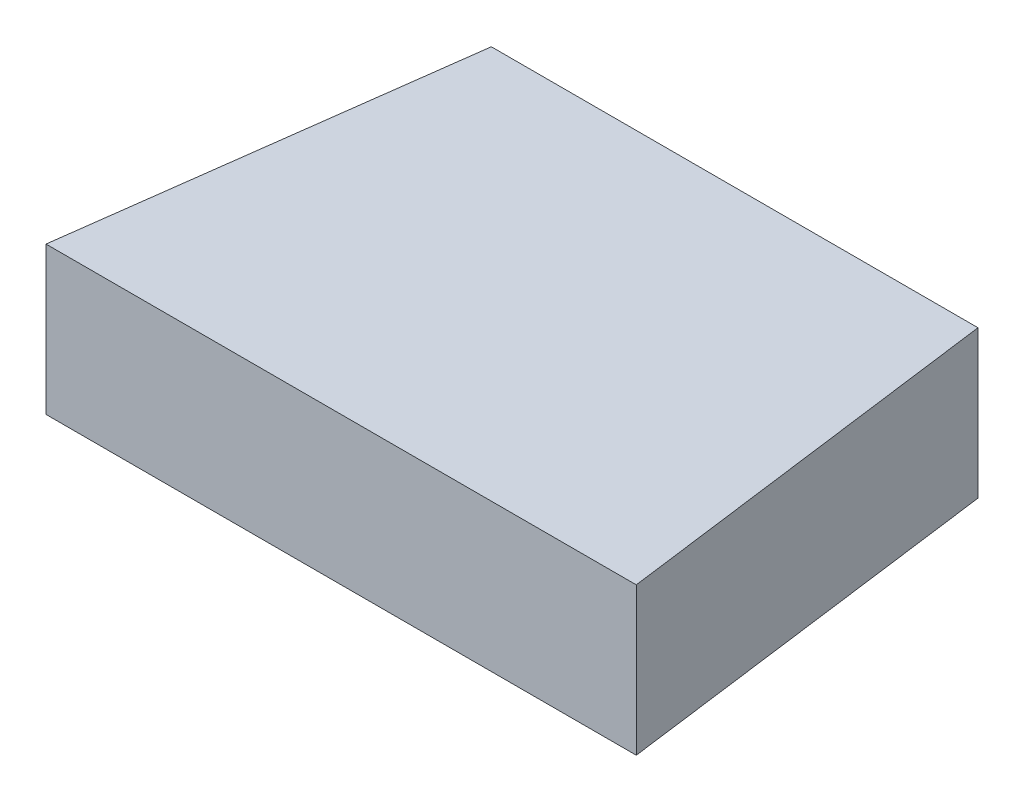
SolidWorks part; units mm, degrees
ref_plane "Front" through (0, 0, 0) normal (0, 0, 1) x (1, 0, 0)
ref_plane "Top" through (0, 0, 0) normal (0, 1, 0) x (1, 0, 0)
ref_plane "Right" through (0, 0, 0) normal (1, 0, 0) x (0, 0, -1)
sketch "Sketch1" plane through (0, 0, 0) normal (0, 1, 0) x (1, 0, 0)
  line L0 (31.4121, -238.5982) -> (92.0955, -222.3382) construction
  line L1 (289.3982, -38.1) -> (289.3982, 38.1) construction
  line L2 (289.3982, 38.1) -> (269.6762, 111.7035) construction
  line L3 (269.6762, 111.7035) -> (231.5762, 177.6947) construction
  line L4 (231.5762, 177.6947) -> (177.6947, 231.5762) construction
  line L5 (177.6947, 231.5762) -> (111.7035, 269.6762) construction
  line L6 (111.7035, 269.6762) -> (38.1, 289.3982) construction
  line L7 (38.1, 289.3982) -> (-38.1, 289.3982) construction
  line L8 (-38.1, 289.3982) -> (-111.7035, 269.6762) construction
  line L9 (-111.7035, 269.6762) -> (-177.6947, 231.5762) construction
  line L10 (-177.6947, 231.5762) -> (-231.5762, 177.6947) construction
  line L11 (-231.5762, 177.6947) -> (-269.6762, 111.7035) construction
  line L12 (-269.6762, 111.7035) -> (-289.3982, 38.1) construction
  line L13 (-289.3982, 38.1) -> (-289.3982, -38.1) construction
  line L14 (-289.3982, -38.1) -> (-269.6762, -111.7035) construction
  line L15 (-269.6762, -111.7035) -> (-231.5762, -177.6947) construction
  line L16 (-231.5762, -177.6947) -> (-177.6947, -231.5762) construction
  line L17 (-177.6947, -231.5762) -> (-111.7035, -269.6762) construction
  line L18 (-111.7035, -269.6762) -> (-38.1, -289.3982) construction
  line L19 (-38.1, -289.3982) -> (38.1, -289.3982)
  line L20 (38.1, -289.3982) -> (111.7035, -269.6762) construction
  line L21 (111.7035, -269.6762) -> (177.6947, -231.5762) construction
  line L22 (177.6947, -231.5762) -> (231.5762, -177.6947) construction
  line L23 (231.5762, -177.6947) -> (269.6762, -111.7035) construction
  line L24 (269.6762, -111.7035) -> (289.3982, -38.1) construction
  line L25 (92.0955, -222.3382) -> (146.5028, -190.9261) construction
  line L26 (146.5028, -190.9261) -> (190.9261, -146.5028) construction
  line L27 (190.9261, -146.5028) -> (222.3382, -92.0955) construction
  line L28 (222.3382, -92.0955) -> (238.5982, -31.4121) construction
  line L29 (238.5982, -31.4121) -> (238.5982, 31.4121) construction
  line L30 (238.5982, 31.4121) -> (222.3382, 92.0955) construction
  line L31 (222.3382, 92.0955) -> (190.9261, 146.5028) construction
  line L32 (190.9261, 146.5028) -> (146.5028, 190.9261) construction
  line L33 (146.5028, 190.9261) -> (92.0955, 222.3382) construction
  line L34 (92.0955, 222.3382) -> (31.4121, 238.5982) construction
  line L35 (31.4121, 238.5982) -> (-31.4121, 238.5982) construction
  line L36 (-31.4121, 238.5982) -> (-92.0955, 222.3382) construction
  line L37 (-92.0955, 222.3382) -> (-146.5028, 190.9261) construction
  line L38 (-146.5028, 190.9261) -> (-190.9261, 146.5028) construction
  line L39 (-190.9261, 146.5028) -> (-222.3382, 92.0955) construction
  line L40 (-222.3382, 92.0955) -> (-238.5982, 31.4121) construction
  line L41 (-238.5982, 31.4121) -> (-238.5982, -31.4121) construction
  line L42 (-238.5982, -31.4121) -> (-222.3382, -92.0955) construction
  line L43 (-222.3382, -92.0955) -> (-190.9261, -146.5028) construction
  line L44 (-190.9261, -146.5028) -> (-146.5028, -190.9261) construction
  line L45 (-146.5028, -190.9261) -> (-92.0955, -222.3382) construction
  line L46 (-92.0955, -222.3382) -> (-31.4121, -238.5982) construction
  line L47 (-31.4121, -238.5982) -> (31.4121, -238.5982)
  line L48 (0, 0) -> (-31.4121, -238.5982) construction
  line L49 (0, 0) -> (31.4121, -238.5982) construction
  line L50 (-31.4121, -238.5982) -> (-38.1, -289.3982)
  line L52 (31.4121, -238.5982) -> (38.1, -289.3982)
  circle A0 centre (0, 0) radius 289.3982 construction
  dimension "D1" = 76.2
  dimension "D2" = 50.8
extrude "Boss-Extrude1" add sketch "Sketch1" along normal blind 19.05
